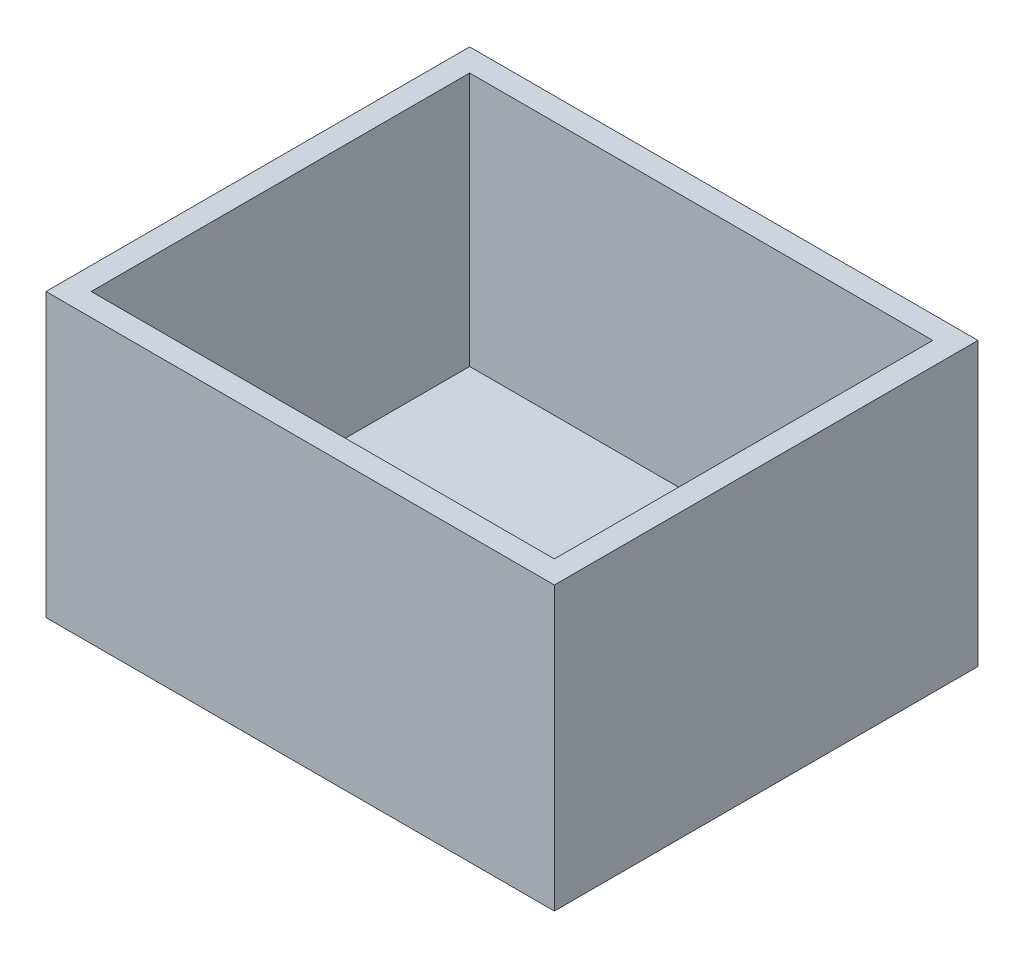
SolidWorks part; units mm, degrees
ref_plane "Front Plane" through (0, 0, 0) normal (0, 0, 1) x (1, 0, 0)
ref_plane "Top Plane" through (0, 0, 0) normal (0, 1, 0) x (1, 0, 0)
ref_plane "Right Plane" through (0, 0, 0) normal (1, 0, 0) x (0, 0, -1)
sketch "Sketch1" plane through (0, 0, 0) normal (0, 0, 1) x (1, 0, 0)
  line L1 (-45, -25) -> (45, -25)
  line L2 (-45, -25) -> (-45, 25)
  line L3 (-45, 25) -> (45, 25)
  line L4 (45, -25) -> (45, 25)
  line L5 (-45, -25) -> (45, 25) construction
  line L6 (-45, 25) -> (45, -25) construction
  point P0 (0, 0)
  dimension "D1" = 50
  dimension "D2" = 90
extrude "Boss-Extrude1" add sketch "Sketch1" along normal blind 75
sketch "Sketch2" plane through (0, 25, 0) normal (0, 1, 0) x (1, 0, 0)
  line L0 (45, 0) -> (-45, 0) construction
  line L1 (-41, -71) -> (41, -71)
  line L2 (-41, -71) -> (-41, -4)
  line L3 (-41, -4) -> (41, -4)
  line L4 (41, -71) -> (41, -4)
  line L5 (-45, -75) -> (-45, 0) construction
  line L6 (45, -75) -> (45, 0) construction
  line L7 (45, -75) -> (-45, -75) construction
  dimension "D1" = 4
  dimension "D2" = 4
  dimension "D3" = 4
  dimension "D4" = 4
extrude "Cut-Extrude1" cut sketch "Sketch2" against normal blind 45
sketch "Sketch3" plane through (0, -20, 0) normal (0, 1, 0) x (1, 0, 0)
  line L0 (-41, -71) -> (41, -71) construction
  line L1 (-1.8776, -71) -> (3.1224, -71)
  line L2 (-1.8776, -71) -> (-1.8776, -66)
  line L3 (-1.8776, -66) -> (3.1224, -66)
  line L4 (3.1224, -71) -> (3.1224, -66)
  dimension "D1" = 5
  dimension "D2" = 5
extrude "Cut-Extrude2" cut sketch "Sketch3" against normal blind 45
sketch "Sketch5" plane through (0, 0, 0) normal (0, 0, -1) x (-1, 0, 0)
  text T0 "    A.P. \r\n SINGH\r\n\r\n" font "Century Gothic" height in points 42
extrude "Boss-Extrude3" add sketch "Sketch5" along normal blind 1.5
